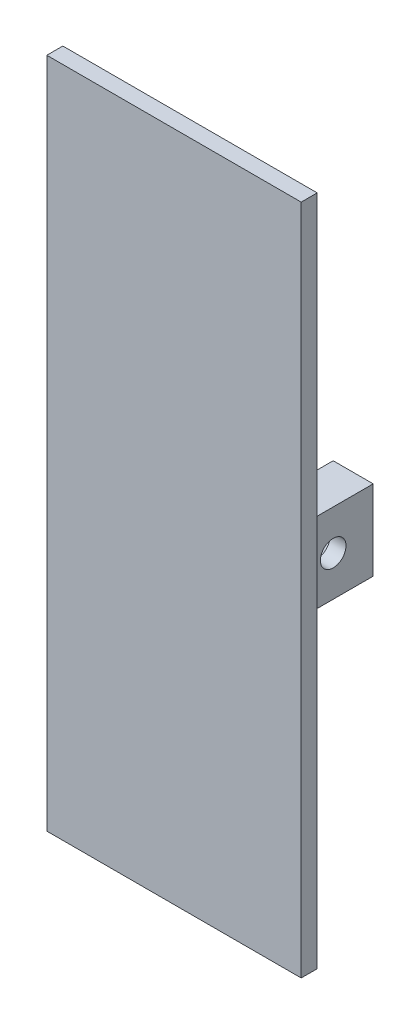
SolidWorks part; units mm, degrees
ref_plane "Front Plane" through (0, 0, 0) normal (0, 0, 1) x (1, 0, 0)
ref_plane "Top Plane" through (0, 0, 0) normal (0, 1, 0) x (1, 0, 0)
ref_plane "Right Plane" through (0, 0, 0) normal (1, 0, 0) x (0, 0, -1)
sketch "Sketch1" plane through (0, 0, 0) normal (0, 0, 1) x (1, 0, 0)
  line L1 (15.9, -42) -> (-15.9, -42)
  line L2 (15.9, -42) -> (15.9, 42)
  line L3 (15.9, 42) -> (-15.9, 42)
  line L4 (-15.9, -42) -> (-15.9, 42)
  line L5 (15.9, -42) -> (-15.9, 42) construction
  line L6 (15.9, 42) -> (-15.9, -42) construction
  point P0 (0, 0)
  dimension "D1" = 84
  dimension "D2" = 31.8
extrude "Boss-Extrude1" add sketch "Sketch1" along normal blind 2
sketch "Sketch2" plane through (0, 0, 0) normal (0, 0, -1) x (-1, 0, 0)
  line L0 (-15.9, -42) -> (-15.9, 42) construction
  line L1 (13.9, -39.95) -> (-13.9, -39.95)
  line L2 (13.9, -39.95) -> (13.9, 39.95)
  line L3 (13.9, 39.95) -> (-13.9, 39.95)
  line L4 (-13.9, -39.95) -> (-13.9, 39.95)
  line L5 (13.9, -39.95) -> (-13.9, 39.95) construction
  line L6 (13.9, 39.95) -> (-13.9, -39.95) construction
  point P0 (0, 0)
  dimension "D1" = 79.9
  dimension "D2" = 2
extrude "Boss-Extrude2" add sketch "Sketch2" along normal blind 0.001
sketch "Sketch3" plane through (0, 0, 0) normal (0, 0, -1) x (-1, 0, 0)
  line L0 (-13.9, -39.95) -> (-13.9, 39.95) construction
  line L1 (-13.9, 5) -> (-8.9, 5)
  line L2 (-13.9, 5) -> (-13.9, -5)
  line L3 (-13.9, -5) -> (-8.9, -5)
  line L4 (-8.9, 5) -> (-8.9, -5)
  dimension "D1" = 5
  dimension "D2" = 10
  dimension "D3" = 5
extrude "Boss-Extrude3" add sketch "Sketch3" along normal blind 9
sketch "Sketch4" plane through (8.9, 0, 0) normal (-1, 0, 0) x (0, 0, 1)
  line L0 (-9, 5) -> (-0.001, 5) construction
  line L1 (-2.4123, 2.75) -> (-5.5877, 2.75)
  line L2 (-5.5877, 2.75) -> (-7.1754, 0)
  line L3 (-7.1754, 0) -> (-5.5877, -2.75)
  line L4 (-5.5877, -2.75) -> (-2.4123, -2.75)
  line L5 (-2.4123, -2.75) -> (-0.8246, 0)
  line L6 (-0.8246, 0) -> (-2.4123, 2.75)
  line L8 (2, 42) -> (2, -42) construction
  circle A0 centre (-4, 0) radius 2.75 construction
  dimension "D1" = 5.5
  dimension "D2" = 6
extrude "Cut-Extrude1" cut sketch "Sketch4" against normal blind 3
sketch "Sketch5" plane through (11.9, 0, 0) normal (-1, 0, 0) x (0, 0, 1)
  line L1 (-9, 5) -> (-0.001, 5) construction
  line L2 (0, -5) -> (0, 5) construction
  circle A0 centre (-4, 0) radius 1.6
  dimension "D1" = 4
  dimension "D2" = 5
  dimension "D3" = 3.2
extrude "Cut-Extrude2" cut sketch "Sketch5" against normal up to surface (2 mm away) up to face at (13.9, 0, -2.2505)
